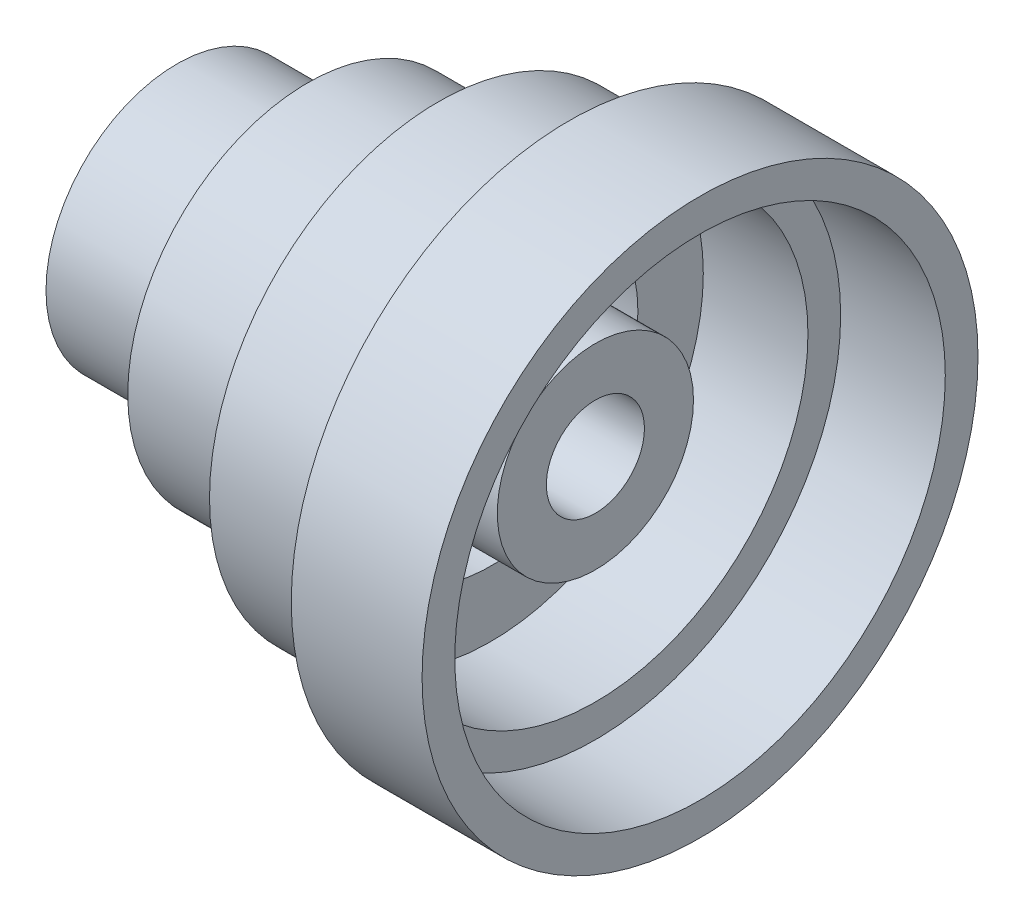
SolidWorks part; units mm, degrees
ref_plane "Front Plane" through (0, 0, 0) normal (0, 0, 1) x (1, 0, 0)
ref_plane "Top Plane" through (0, 0, 0) normal (0, 1, 0) x (1, 0, 0)
ref_plane "Right Plane" through (0, 0, 0) normal (1, 0, 0) x (0, 0, -1)
sketch "Sketch1" plane through (0, 0, 0) normal (0, 0, 1) x (1, 0, 0)
  line L0 (0, 0) -> (4064, 0) construction
  line L1 (0, 381) -> (0, 1016)
  line L2 (0, 1016) -> (1016, 1016)
  line L3 (1016, 1016) -> (1016, 1397)
  line L4 (1016, 1397) -> (2032, 1397)
  line L5 (2032, 1397) -> (2032, 1778)
  line L6 (2032, 1778) -> (3048, 1778)
  line L7 (3048, 1778) -> (3048, 2159)
  line L8 (3048, 2159) -> (4064, 2159)
  line L9 (4064, 2159) -> (4064, 381)
  line L10 (4064, 381) -> (0, 381)
  dimension "D1" = 1016
  dimension "D2" = 381
  dimension "D3" = 1016
  dimension "D4" = 1397
revolve "Revolve1" add sketch "Sketch1" angle 360 about L0
sketch "Sketch2" plane through (4064, 0, 0) normal (1, 0, 0) x (0, 0, -1)
  circle A0 centre (0, 0) radius 1905
  dimension "D1" = 3810
sketch "Sketch5" plane through (4064, 0, 0) normal (1, 0, 0) x (0, 0, -1)
  circle A0 centre (0, 0) radius 1905
extrude "Cut-Extrude2" cut sketch "Sketch5" against normal blind 812.8
sketch "Sketch6" plane through (3251.2, 0, 0) normal (1, 0, 0) x (0, 0, -1)
  circle A0 centre (0, 0) radius 1651
extrude "Cut-Extrude3" cut sketch "Sketch6" against normal blind 812.8
sketch "Sketch7" plane through (2438.4, 0, 0) normal (1, 0, 0) x (0, 0, -1)
  circle A0 centre (0, 0) radius 1397
sketch "Sketch8" plane through (2438.4, 0, 0) normal (1, 0, 0) x (0, 0, -1)
  circle A1 centre (0, 0) radius 1143
extrude "Cut-Extrude5" cut sketch "Sketch8" against normal blind 812.8
sketch "Sketch10" plane through (3251.2, 0, 0) normal (1, 0, 0) x (0, 0, -1)
  circle A0 centre (0, 0) radius 762
sketch "Sketch11" plane through (3251.2, 0, 0) normal (1, 0, 0) x (0, 0, -1)
  circle A0 centre (0, 0) radius 762
extrude "Boss-Extrude2" add sketch "Sketch11" against normal through all
sketch "Sketch12" plane through (0, 0, 0) normal (-1, 0, 0) x (0, 0, 1)
  circle A0 centre (0, 0) radius 381
extrude "Cut-Extrude7" cut sketch "Sketch12" against normal up to next and the other way through all contours A0
sketch "Sketch14" plane through (0, 0, 0) normal (-1, 0, 0) x (0, 0, 1)
  line L0 (-76.2, -457.2) -> (76.2, -457.2)
  line L2 (-76.2, -457.2) -> (-76.2, -373.3022)
  line L4 (76.2, -457.2) -> (76.2, -373.3022)
  circle A0 centre (0, 0) radius 381 construction
  dimension "D1" = 76.2
  dimension "D2" = 457.2
sketch "Sketch16" plane through (3251.2, 0, 0) normal (1, 0, 0) x (0, 0, -1)
  line L0 (-76.2, -457.2) -> (76.2, -457.2)
  line L4 (-76.2, -457.2) -> (-76.2, -373.3022)
  line L6 (76.2, -457.2) -> (76.2, -373.3022)
